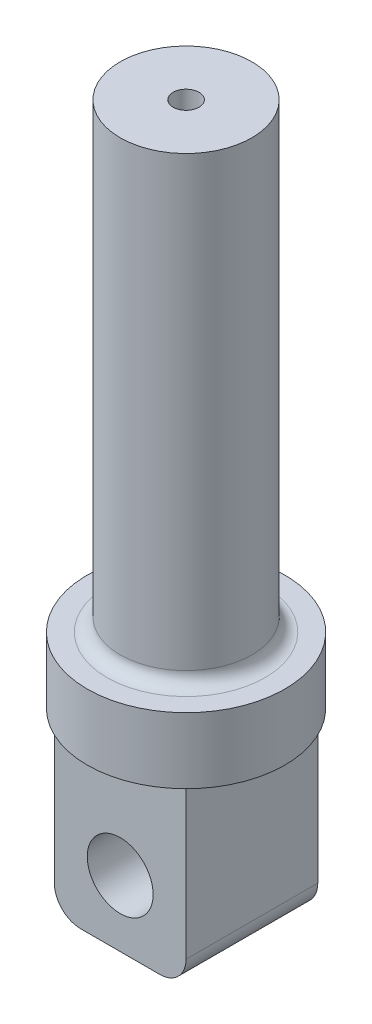
SolidWorks part; units mm, degrees
material "6061 Alloy"
ref_plane "Front Plane" through (0, 0, 0) normal (0, 0, 1) x (1, 0, 0)
ref_plane "Top Plane" through (0, 0, 0) normal (0, 1, 0) x (1, 0, 0)
ref_plane "Right Plane" through (0, 0, 0) normal (1, 0, 0) x (0, 0, -1)
sketch "Sketch3" plane through (0, 0, 0) normal (0, 1, 0) x (1, 0, 0)
  line L0 (0, 0) -> (12.7, 0)
  line L1 (-27.94, 0) -> (27.94, 0) construction
  line L2 (12.7, 0) -> (12.7, 12.7)
  line L3 (12.7, 12.7) -> (0, 12.7)
  line L4 (0, -27.94) -> (0, 27.94) construction
  line L5 (0, 12.7) -> (-12.7, 12.7)
  line L6 (-12.7, 12.7) -> (-12.7, 0)
  line L7 (-12.7, 0) -> (-12.7, -12.7)
  line L8 (-12.7, -12.7) -> (0, -12.7)
  line L9 (0, -12.7) -> (12.7, -12.7)
  line L10 (12.7, -12.7) -> (12.7, 0)
  dimension "D1" = 25.4
extrude "Boss-Extrude1" add sketch "Sketch3" along normal blind 34.317 contours L2 L3 L5 L6 L7 L8 L9 L10
sketch "Sketch4" plane through (0, 34.317, 0) normal (0, 1, 0) x (1, 0, 0)
  circle A0 centre (0, 0) radius 19.05
  dimension "D1" = 38.1
extrude "Boss-Extrude2" add sketch "Sketch4" along normal blind 12.7 contours A0
sketch "Sketch6" plane through (0, 47.017, 0) normal (0, 1, 0) x (1, 0, 0)
  circle A0 centre (0, 0) radius 12.7
  dimension "D1" = 25.4
extrude "Boss-Extrude3" add sketch "Sketch6" along normal blind 88.9 contours A0
sketch "Sketch7" plane through (0, 0, 12.7) normal (0, 0, 1) x (1, 0, 0)
  line L0 (0, 0) -> (0, 12.7)
  line L1 (0, -20.955) -> (0, 20.955) construction
  line L3 (7.3323, 12.7) -> (3.6662, 19.05)
  line L4 (3.6662, 19.05) -> (-3.6662, 19.05)
  line L5 (-3.6662, 19.05) -> (-7.3323, 12.7)
  line L6 (-7.3323, 12.7) -> (-3.6662, 6.35)
  line L7 (-3.6662, 6.35) -> (3.6662, 6.35)
  line L8 (3.6662, 6.35) -> (7.3323, 12.7)
  circle A0 centre (0, 12.7) radius 6.35 construction
  circle A1 centre (0, 12.7) radius 6.35
  point P5 (-5.4993, 15.875)
  dimension "D1" = 12.7
  dimension "D3" = 12.7
  dimension "D2" = 12.7
extrude "Cut-Extrude1" cut sketch "Sketch7" against normal through all
fillet "Fillet1" radius 5.08 2 edges at (12.7, 0, 0) (-12.7, 0, 0)
sketch "Sketch10" plane through (0, 135.917, 0) normal (0, 1, 0) x (1, 0, 0)
  line L0 (0, 0) -> (6.35, 0)
  line L1 (-20.955, 0) -> (20.955, 0) construction
  line L2 (0, 0) -> (-6.35, 0)
  dimension "D1" = 12.7
fillet "Fillet2" radius 2.54 1 edges at (0, 47.017, 12.7)
sketch "Sketch11" plane through (0, 135.917, 0) normal (0, 1, 0) x (1, 0, 0)
  circle A0 centre (0, 0) radius 3.175
  point P0 (0, 0)
  dimension "D1" = 6.35
hole_wizard "M6x1.0 Tapped Hole1" positions "Sketch11" profile "Sketch13" tap size "M6x1.0" standard "ANSI Metric"
sketch "Sketch13" plane through (0, 135.917, 0) normal (1, 0, 0) x (0, 0, 1)
  line L0 (0, 0) -> (0, 42.6502)
  line L1 (0, 42.6502) -> (2.5, 41.148)
  line L2 (2.5, 41.148) -> (2.5, 0)
  line L5 (2.5, 0) -> (0, 0)
  line L10 (0, 42.6502) -> (-2.5, 41.148) construction
  line L11 (0, -6.35) -> (0, 107.95) construction
  dimension "Tap Drill Dia." = 5
  dimension "Tap Drill Depth" = 41.148
  dimension "Drill Angle" = 118
equation "\"Trochanter-Iliac-diff\"= 4in"
equation "\"rodsquareside\"= 1in"
equation "\"axisdiff\"= 2.6489381in"
equation "\"hexsize\"= 0.5in"
equation "\"hexcentertobottom\"= 0.5in"
equation "\"D1@Sketch3\"=\"rodsquareside\""
equation "\"collarheight\"= 0.5in"
equation "\"D1@Boss-Extrude1\"=\"Trochanter-Iliac-diff\"-\"collarheight\"-\"axisdiff\"+\"hexcentertobottom\""
equation "\"rodthickness\"= 1.5in"
equation "\"plateheight\"= 3.5in"
equation "\"lidscrewholedepth\"= 0.5in"
equation "\"D1@Sketch4\"=\"rodthickness\""
equation "\"D1@Boss-Extrude2\"=\"collarheight\""
equation "\"rodaxlethickness\"= 1in"
equation "\"D1@Sketch6\"=\"rodaxlethickness\""
equation "\"D1@Boss-Extrude3\"=\"plateheight\""
equation "\"D1@Sketch7\"=\"hexcentertobottom\""
equation "\"D2@Sketch7\"=\"hexsize\""
equation "\"rodsquarefiletradius\"= 0.2in"
equation "\"D1@Fillet1\"=\"rodsquarefiletradius\""
equation "\"lidscrewholediff\"= 0.5in"
equation "\"D1@Sketch10\"=\"lidscrewholediff\""
equation "\"filetradius\"= 0.1in"
equation "\"D1@Fillet2\"=\"filetradius\""
